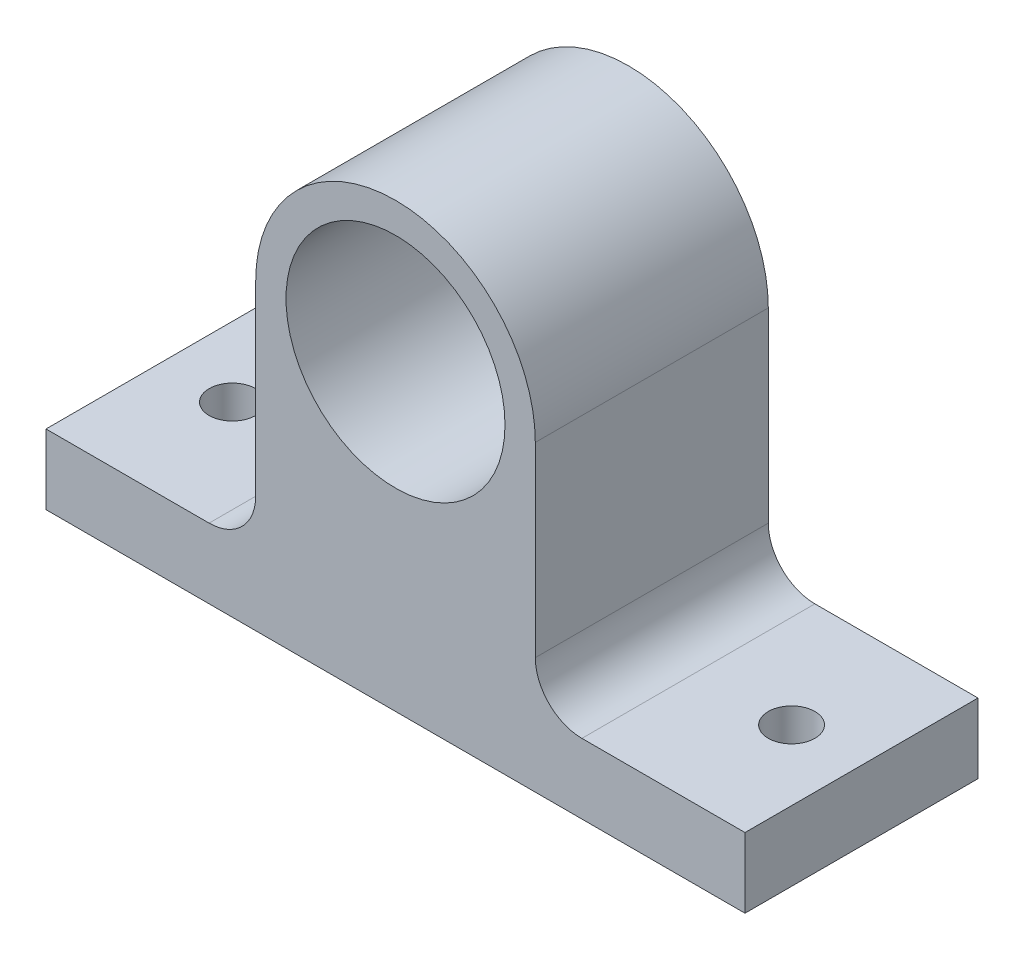
SolidWorks part; units mm, degrees
material "1.0037 (S235JR)"
ref_plane "Ön Düzlem" through (0, 0, 0) normal (0, 0, 1) x (1, 0, 0)
ref_plane "Üst Düzlem" through (0, 0, 0) normal (0, 1, 0) x (1, 0, 0)
ref_plane "Sağ Düzlem" through (0, 0, 0) normal (1, 0, 0) x (0, 0, -1)
sketch "Çizim1" plane through (0, 0, 0) normal (0, 0, 1) x (1, 0, 0)
  line L0 (-30, 7.5) -> (-30, 57.5)
  line L1 (75, -7.5) -> (-75, -7.5)
  line L2 (75, -7.5) -> (75, 7.5)
  line L3 (75, 7.5) -> (30, 7.5)
  line L4 (-75, -7.5) -> (-75, 7.5)
  line L5 (75, -7.5) -> (-75, 7.5) construction
  line L6 (75, 7.5) -> (-75, -7.5) construction
  line L7 (-30, 7.5) -> (-75, 7.5)
  line L8 (30, 57.5) -> (30, 7.5)
  arc A0 (30, 57.5) -> (-30, 57.5) centre (0, 57.5) ccw
  circle A1 centre (0, 57.5) radius 23.5
  point P0 (0, 0)
  dimension "D6" = 47
  dimension "D1" = 150
  dimension "D2" = 15
  dimension "D3" = 45
  dimension "D4" = 60
  dimension "D5" = 65
extrude "Yükseklik-Ekstrüzyon1" add sketch "Çizim1" along normal blind 50
fillet "Radyus1" radius 10 2 edges at (-30, 7.5, 25) (30, 7.5, 25)
sketch "Çizim2" plane through (0, 7.5, 0) normal (0, 1, 0) x (1, 0, 0)
  line L0 (-75, -50) -> (-75, 0) construction
  line L1 (-40, 0) -> (-75, 0) construction
  line L2 (0, 30.4175) -> (0, -83.3074) construction
  circle A0 centre (-60, -25) radius 5
  circle A1 centre (60, -25) radius 5
  dimension "D1" = 10
  dimension "D2" = 15
  dimension "D3" = 25
extrude "Kes-Ekstrüzyon1" cut sketch "Çizim2" against normal blind 50
